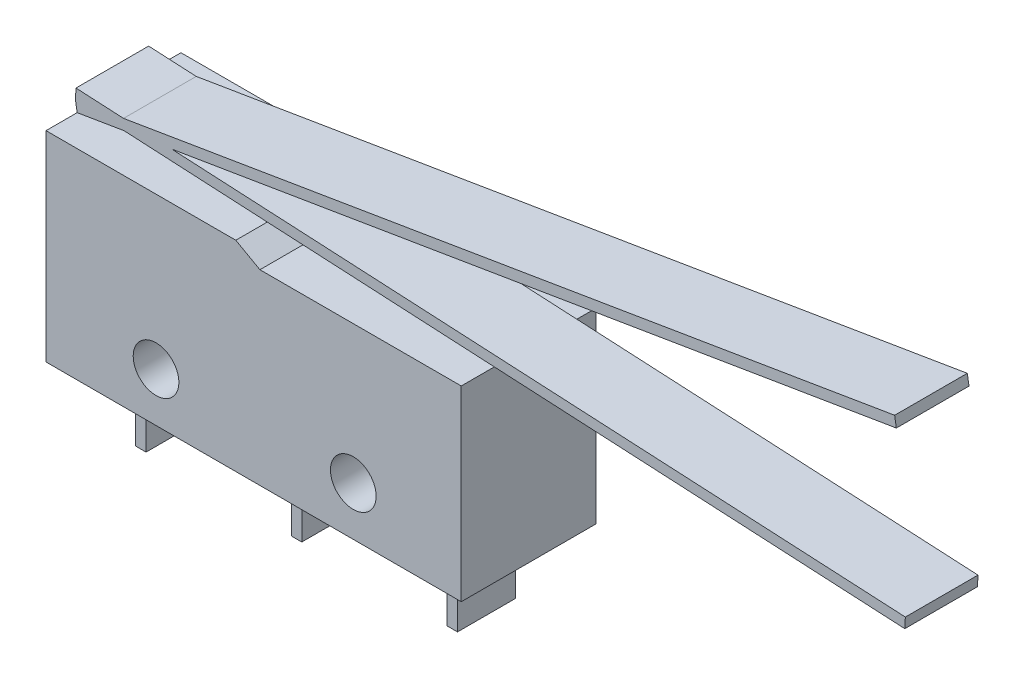
SolidWorks part; units mm, degrees
ref_plane "Plan de face" through (0, 0, 0) normal (0, 0, 1) x (1, 0, 0)
ref_plane "Plan de dessus" through (0, 0, 0) normal (0, 1, 0) x (1, 0, 0)
ref_plane "Plan de droite" through (0, 0, 0) normal (1, 0, 0) x (0, 0, -1)
sketch "Esquisse1" plane through (0, 0, 0) normal (0, 0, 1) x (1, 0, 0)
  line L0 (0, 0) -> (20, 0)
  line L1 (20, 0) -> (20, 9)
  line L2 (20, 9) -> (10.3025, 9)
  line L3 (10.3025, 9) -> (9.1427, 9.65)
  line L4 (9.1427, 9.65) -> (0, 9.65)
  line L5 (0, 9.65) -> (0, 0)
  line L6 (14.8, 2.35) -> (5.3, 2.35) construction
  circle A0 centre (14.8, 2.35) radius 1.1
  circle A1 centre (5.3, 2.35) radius 1.1
  dimension "D4" = 2.2
  dimension "D1" = 20
  dimension "D2" = 9
  dimension "D3" = 9.65
  dimension "D5" = 2.35
  dimension "D6" = 5.2
  dimension "D7" = 9.5
extrude "Extrusion1" add sketch "Esquisse1" along normal blind 6.5
sketch "Esquisse2" plane through (0, 0, 6.5) normal (0, 0, 1) x (1, 0, 0)
  line L0 (0, 9.65) -> (39.4564, 16.2221)
  line L1 (39.4564, 16.2221) -> (39.3742, 16.7153)
  line L2 (39.3742, 16.7153) -> (-0.0822, 10.1432)
  line L3 (-0.0822, 10.1432) -> (0, 9.65)
  dimension "D1" = 40
  dimension "D2" = 0.5
extrude "Extrusion2" add sketch "Esquisse2" along direction (0, 0, 1) on the side against the normal blind 3.5 from offset 1.5
sketch "Esquisse3" plane through (0, 0, 6.5) normal (0, 0, 1) x (1, 0, 0)
  line L0 (-0.056, 10.6493) -> (39.8892, 8.5559)
  line L1 (39.8892, 8.5559) -> (39.863, 8.0566)
  line L2 (39.863, 8.0566) -> (-0.0822, 10.15)
  line L3 (-0.0822, 10.15) -> (-0.056, 10.6493)
  line L4 (0, 9.65) -> (0, 0) construction
  dimension "D1" = 87
  dimension "D2" = 0.5
  dimension "D3" = 0.5
  dimension "D4" = 40
extrude "Extrusion3" add sketch "Esquisse3" against normal blind 3.5 from offset 1.5
sketch "Esquisse4" plane through (0, 0, 0) normal (0, -1, 0) x (1, 0, 0)
  line L0 (2.47, 4.65) -> (17.97, 4.65) construction
  line L1 (2.47, 4.65) -> (2.97, 4.65)
  line L2 (2.47, 4.65) -> (2.47, 1.85)
  line L3 (2.47, 1.85) -> (2.97, 1.85)
  line L4 (2.97, 4.65) -> (2.97, 1.85)
  line L5 (9.97, 4.65) -> (10.47, 4.65)
  line L6 (9.97, 4.65) -> (9.97, 1.85)
  line L7 (9.97, 1.85) -> (10.47, 1.85)
  line L8 (10.47, 4.65) -> (10.47, 1.85)
  line L9 (17.47, 4.65) -> (17.97, 4.65)
  line L10 (17.47, 4.65) -> (17.47, 1.85)
  line L11 (17.47, 1.85) -> (17.97, 1.85)
  line L12 (17.97, 4.65) -> (17.97, 1.85)
  line L13 (0, 6.5) -> (20, 6.5) construction
  line L14 (0, 6.5) -> (0, 0) construction
  dimension "D1" = 0.5
  dimension "D2" = 2.8
  dimension "D3" = 1.85
  dimension "D4" = 7.5
  dimension "D5" = 7.5
  dimension "D6" = 2.47
extrude "Extrusion4" add sketch "Esquisse4" along normal blind 3.2
